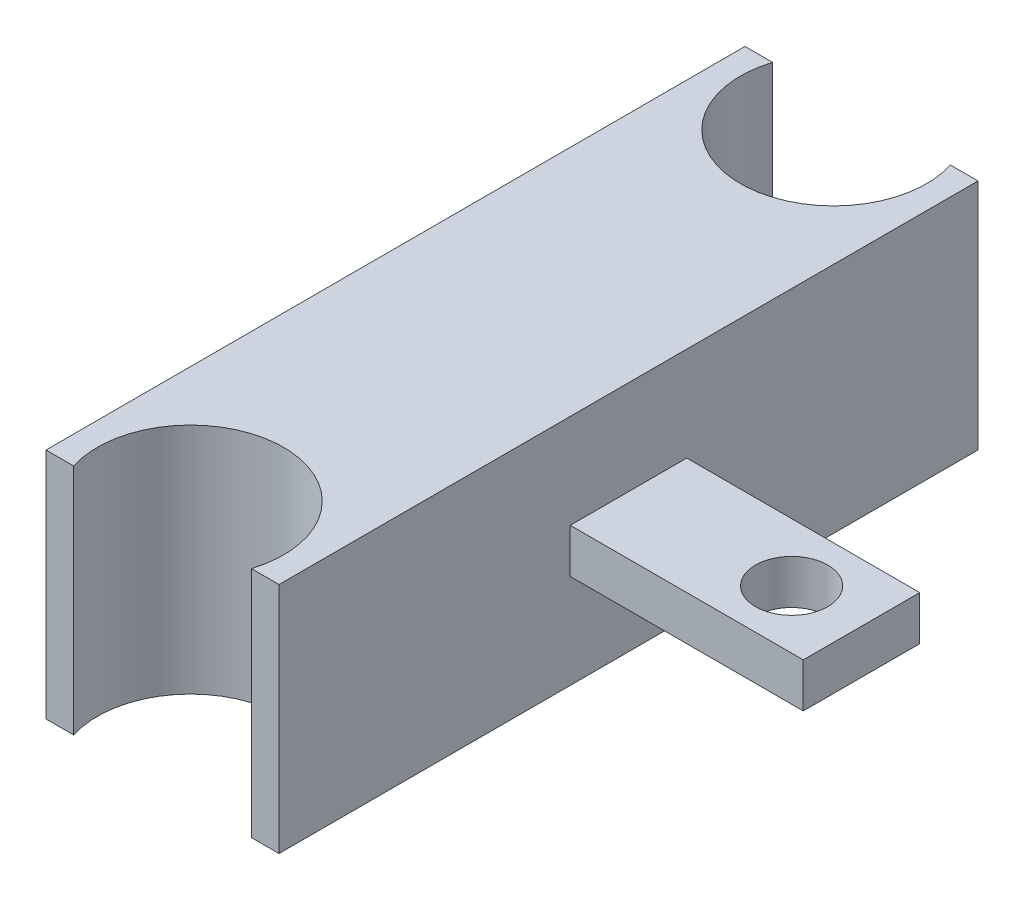
SolidWorks part; units mm, degrees
ref_plane "前视基准面" through (0, 0, 0) normal (0, 0, 1) x (1, 0, 0)
ref_plane "上视基准面" through (0, 0, 0) normal (0, 1, 0) x (1, 0, 0)
ref_plane "右视基准面" through (0, 0, 0) normal (1, 0, 0) x (0, 0, -1)
other "Configuration Table"
sketch "草图1" plane through (0, 0, 0) normal (0, 1, 0) x (1, 0, 0)
  line L1 (0, 0) -> (10, 0)
  line L2 (0, 0) -> (0, 5)
  line L3 (0, 5) -> (10, 5)
  line L4 (10, 0) -> (10, 5)
  circle A0 centre (7, 2.5) radius 1.55
  dimension "D4" = 3.1
  dimension "D1" = 5
  dimension "D2" = 10
  dimension "D3" = 3
  dimension "D5" = 2.5
extrude "凸台-拉伸1" add sketch "草图1" along normal blind 1.9 contours L2 L3 L4 L1
sketch "草图2" plane through (0, 0, 0) normal (-1, 0, 0) x (0, 0, 1)
  line L0 (-5, 1.9) -> (0, 0) construction
  line L1 (0, 1.9) -> (-5, 0) construction
  line L3 (12.5, -4.05) -> (-17.5, -4.05)
  line L4 (12.5, -4.05) -> (12.5, 5.95)
  line L5 (12.5, 5.95) -> (-17.5, 5.95)
  line L6 (-17.5, -4.05) -> (-17.5, 5.95)
  line L7 (12.5, -4.05) -> (-17.5, 5.95) construction
  line L8 (12.5, 5.95) -> (-17.5, -4.05) construction
  point P8 (-2.5, 0.95)
  dimension "D1" = 10
  dimension "D2" = 30
extrude "凸台-拉伸2" add sketch "草图2" along normal blind 10
sketch "草图3" plane through (0, 5.95, 0) normal (0, 1, 0) x (1, 0, 0)
  line L0 (-5, 17.5) -> (-5, -12.5) construction
  line L1 (-10, 17.5) -> (0, 17.5) construction
  line L2 (-10, -12.5) -> (0, -12.5) construction
  circle A0 centre (-5, 16.3) radius 4
  circle A1 centre (-5, -11.3) radius 4
  dimension "D2" = 8
  dimension "D3" = 8
  dimension "D1" = 1.2
  dimension "D4" = 1.2
extrude "切除-拉伸1" cut sketch "草图3" against normal blind 10 contours A0 | A1
